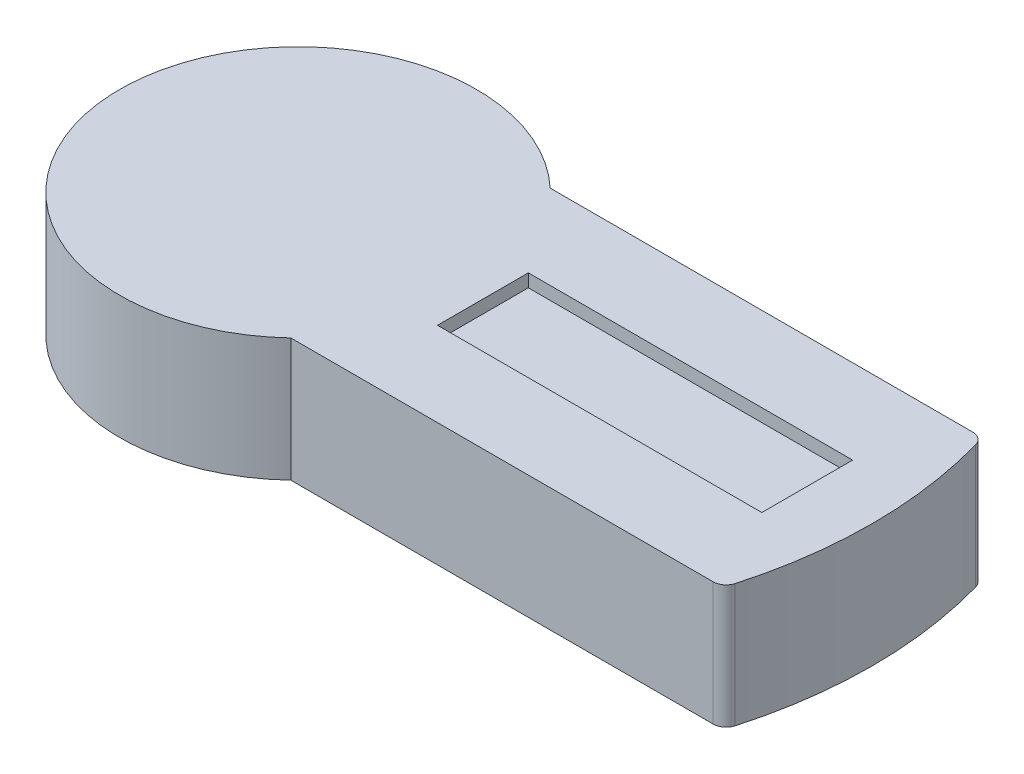
SolidWorks part; units mm, degrees
ref_plane "Front Plane" through (0, 0, 0) normal (0, 0, 1) x (1, 0, 0)
ref_plane "Top Plane" through (0, 0, 0) normal (0, 1, 0) x (1, 0, 0)
ref_plane "Right Plane" through (0, 0, 0) normal (1, 0, 0) x (0, 0, -1)
sketch "Sketch1" plane through (0, 0, 0) normal (0, 1, 0) x (1, 0, 0)
  circle A0 centre (0, 0) radius 13.75
  dimension "D1" = 27.5
extrude "Boss-Extrude1" add sketch "Sketch1" along normal blind 9.5
sketch "Sketch2" plane through (0, 0, 0) normal (0, 1, 0) x (1, 0, 0)
  line L1 (0, 10) -> (44.25, 10)
  line L2 (0, 10) -> (0, -10)
  line L3 (0, -10) -> (44.25, -10)
  line L4 (44.25, 10) -> (44.25, -10)
  dimension "D1" = 20
  dimension "D2" = 44.25
extrude "Boss-Extrude2" add sketch "Sketch2" along normal up to surface (9.5 mm away) contours L1 L4 L3 L2 up to face at (0, 9.5, 13.75)
sketch "Sketch3" plane through (0, 0, 0) normal (1, 0, 0) x (0, 0, -1)
  line L4 (13.75, 0) -> (13.75, 9.5) construction
  line L5 (13.75, 9.5) -> (-13.75, 9.5) construction
  circle A0 centre (0, 4.5) radius 2
  dimension "D1" = 4
  dimension "D2" = 13.75
  dimension "D3" = 5
extrude "Boss-Extrude3" add sketch "Sketch3" against normal offset from surface (16.1265 mm away) 2.5 contours A0
sketch "Sketch4" plane through (0, 9.5, 0) normal (0, 1, 0) x (1, 0, 0)
  line L0 (44.25, 10) -> (44.25, -10) construction
  line L1 (14.25, 3.5) -> (39.25, 3.5)
  line L2 (14.25, 3.5) -> (14.25, -3.5)
  line L3 (14.25, -3.5) -> (39.25, -3.5)
  line L4 (39.25, 3.5) -> (39.25, -3.5)
  line L5 (9.4373, -10) -> (44.25, -10) construction
  dimension "D1" = 7
  dimension "D2" = 25
  dimension "D3" = 5
  dimension "D4" = 6.5
extrude "Cut-Extrude1" cut sketch "Sketch4" against normal blind 1 contours L1 L4 L3 L2
sketch "Sketch5" plane through (0, 9.5, 0) normal (0, 1, 0) x (1, 0, 0)
  line L0 (9.4373, 10) -> (44.25, 10) construction
  line L1 (9.4373, -10) -> (44.25, -10) construction
  line L2 (42.75, 10) -> (47.75, 10)
  line L3 (47.75, 10) -> (47.75, -10)
  line L4 (47.75, -10) -> (42.75, -10)
  line L5 (44.25, 10) -> (44.25, -10) construction
  arc A0 (42.75, 10) -> (42.75, -10) centre (10.1667, 0) cw
  point P11 (44.25, 0)
  dimension "D1" = 1.5
  dimension "D2" = 5
extrude "Cut-Extrude2" cut sketch "Sketch5" against normal through all
fillet "Fillet1" radius 1 2 edges at (42.75, 4.75, -10) (42.75, 4.75, 10)
